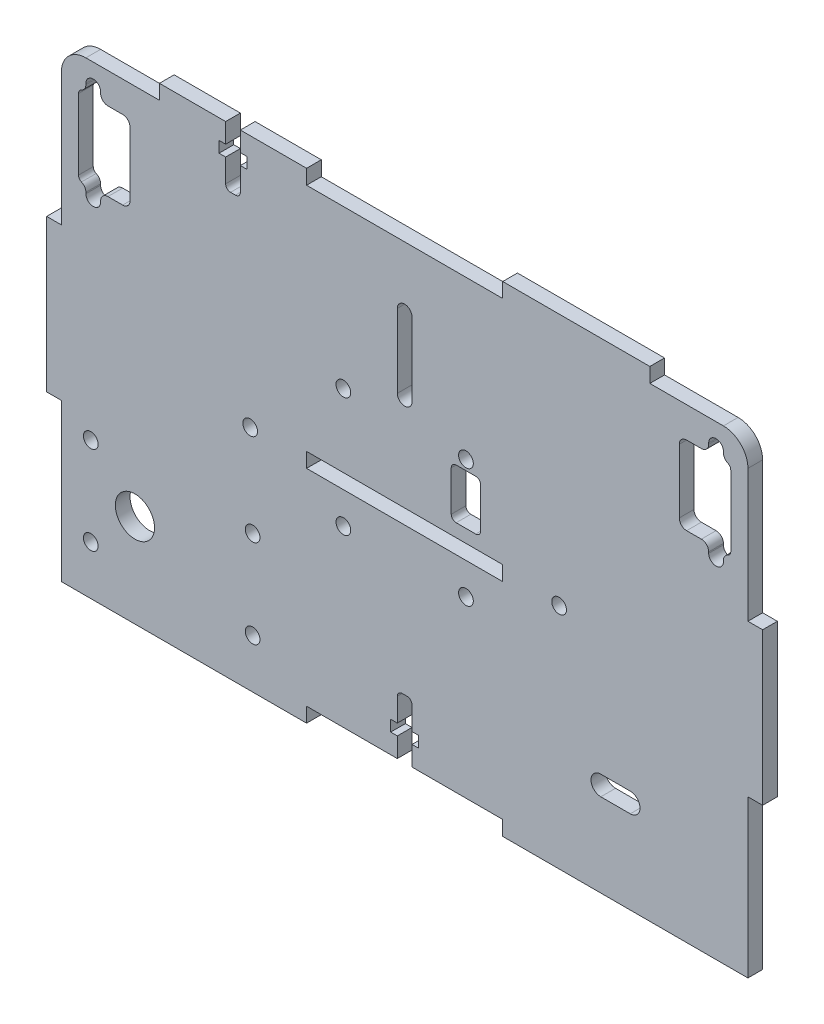
SolidWorks part; units mm, degrees
other "Marcação1"
sketch "Esboço7" plane through (-68, 31.5, 3) normal (-0.6758, 0.2828, 0.6807) x (0.7271, 0.1043, 0.6785)
sketch "Esboço8" plane through (-68, 31.5, 3) normal (-0.6758, 0.2828, 0.6807) x (0.7271, 0.1043, 0.6785)
sketch "Esboço9" plane through (-68, 31.5, 3) normal (-0.6758, 0.2828, 0.6807) x (0.7271, 0.1043, 0.6785)
sketch "Esboço10" plane through (-68, 31.5, 3) normal (-0.6758, 0.2828, 0.6807) x (0.7271, 0.1043, 0.6785)
sketch "Esboço11" plane through (-68, 36.25, 3) normal (-0.6758, 0.2828, 0.6807) x (0.7271, 0.1043, 0.6785)
sketch "Esboço13" plane through (-68, 36.25, 3) normal (-0.6758, 0.2828, 0.6807) x (0.7271, 0.1043, 0.6785)
sketch "Esboço15" plane through (-68, 36.25, 3) normal (-0.6758, 0.2828, 0.6807) x (0.7271, 0.1043, 0.6785)
sketch "Esboço19" plane through (-68, 66.25, 3) normal (-0.6758, 0.2828, 0.6807) x (0.7271, 0.1043, 0.6785)
sketch "Esboço22" plane through (-68, 95.5577, 3) normal (-0.6758, 0.2828, 0.6807) x (0.7271, 0.1043, 0.6785)
material "Acrylic (Medium-high impact)"
ref_plane "Plano frontal" through (0, 0, 0) normal (0, 0, 1) x (1, 0, 0)
ref_plane "Plano superior" through (0, 0, 0) normal (0, 1, 0) x (1, 0, 0)
ref_plane "Plano direito" through (0, 0, 0) normal (1, 0, 0) x (0, 0, -1)
sketch "Esboço1" plane through (0, 0, 0) normal (0, 0, 1) x (1, 0, 0)
  line L6 (70, -47.5) -> (-70, -47.5)
  line L8 (70, -47.5) -> (70, 47.5)
  line L9 (70, 47.5) -> (-70, 47.5)
  line L10 (-70, -47.5) -> (-70, 47.5)
  line L11 (70, -47.5) -> (-70, 47.5) construction
  line L12 (70, 47.5) -> (-70, -47.5) construction
  point P0 (0, 0)
  dimension "D1" = 95
  dimension "D2" = 140
extrude "Ressalto-extrusão1" add sketch "Esboço1" along normal mid plane 3
sketch "Esboço2" plane through (0, 0, 1.5) normal (0, 0, 1) x (1, 0, 0)
  line L1 (-20, -47.5) -> (20, -47.5)
  line L2 (-20, -47.5) -> (-20, -44.5)
  line L3 (-20, -44.5) -> (20, -44.5)
  line L4 (20, -47.5) -> (20, -44.5)
  line L6 (-70, -47.5) -> (70, -47.5) construction
  line L21 (-20, 0.5) -> (20, 0.5)
  line L22 (-20, 0.5) -> (-20, -2.5)
  line L23 (-20, -2.5) -> (20, -2.5)
  line L24 (20, 0.5) -> (20, -2.5)
  line L25 (-20, 0.5) -> (20, -2.5) construction
  line L26 (-20, -2.5) -> (20, 0.5) construction
  line L28 (0, -1.65) -> (0, 1.65) construction
  circle A2 centre (-31.5, -1) radius 1.5
  circle A4 centre (31.5, -1) radius 1.5
  point P6 (0, -44.5)
  point P14 (0, -1)
  point P29 (-20, -1)
  dimension "D4" = 3
  dimension "D8" = 3
  dimension "D9" = 10
  dimension "D2" = 40
  dimension "D3" = 45
  dimension "D6" = 3
  dimension "D13" = 40
extrude "Corte-extrusão1" cut sketch "Esboço2" against normal through all
sketch "Esboço3" plane through (0, 0, 1.5) normal (0, 0, 1) x (1, 0, 0)
  line L0 (70, -47.5) -> (70, 47.5) construction
  line L1 (70, 15.5) -> (73, 15.5)
  line L2 (70, 15.5) -> (70, -15.5)
  line L3 (70, -15.5) -> (73, -15.5)
  line L4 (73, 15.5) -> (73, -15.5)
  line L5 (0, -1.65) -> (0, 1.65) construction
  line L6 (-70, -15.5) -> (-73, -15.5)
  line L7 (-70, 15.5) -> (-73, 15.5)
  line L8 (-70, 15.5) -> (-70, -15.5)
  line L9 (-73, 15.5) -> (-73, -15.5)
  line L10 (70, 47.5) -> (-70, 47.5) construction
  line L11 (-50, 50.5) -> (-20, 50.5)
  line L12 (-50, 50.5) -> (-50, 47.5)
  line L13 (-50, 47.5) -> (-20, 47.5)
  line L14 (-20, 50.5) -> (-20, 47.5)
  line L15 (20, 50.5) -> (20, 47.5)
  line L16 (50, 47.5) -> (20, 47.5)
  line L17 (50, 50.5) -> (50, 47.5)
  line L18 (50, 50.5) -> (20, 50.5)
  line L19 (0, -37.5) -> (0, 37.5) construction
  line L20 (-70, 47.5) -> (-70, -47.5) construction
  point P6 (70, 0)
  point P28 (0, 0)
  dimension "D1" = 3
  dimension "D2" = 31
  dimension "D3" = 3
  dimension "D4" = 30
  dimension "D5" = 20
  dimension "D6" = 20
extrude "Ressalto-extrusão2" add sketch "Esboço3" against normal through all
sketch "Esboço30" plane through (0, 0, -1.5) normal (0, 0, -1) x (-1, 0, 0)
  line L0 (73, 15.5) -> (73, -15.5) construction
  line L1 (70, -47.5) -> (20, -47.5) construction
  circle A0 centre (55, -28.5) radius 4
  dimension "D1" = 8
  dimension "D2" = 18
  dimension "D3" = 19
extrude "Corte-extrusão11" cut sketch "Esboço30" against normal through all both and the other way through all
sketch "Esboço31" plane through (0, 0, -1.5) normal (0, 0, -1) x (-1, 0, 0)
  circle A4 centre (64, -19.5) radius 1.5
  circle A5 centre (64, -37.5) radius 1.5
  circle A6 centre (55, -28.5) radius 4 construction
  circle A7 centre (31, -19.5) radius 1.5
  circle A8 centre (31, -37.5) radius 1.5
  dimension "D1" = 3
  dimension "D2" = 9
  dimension "D3" = 9
  dimension "D4" = 18
  dimension "D5" = 33
extrude "Corte-extrusão12" cut sketch "Esboço31" against normal through all both and the other way through all
sketch "Esboço4" plane through (0, 0, 1.5) normal (0, 0, 1) x (1, 0, 0)
  line L0 (-59, -28.5) -> (-51, -28.5) construction
  line L1 (40, -28.5) -> (46, -28.5) construction
  line L2 (40, -26.5) -> (46, -26.5)
  line L3 (40, -30.5) -> (46, -30.5)
  circle A9 centre (-55, -28.5) radius 4 construction
  circle A10 centre (43, -28.5) radius 2 construction
  arc A11 (40, -26.5) -> (40, -30.5) centre (40, -28.5) ccw
  arc A12 (46, -30.5) -> (46, -26.5) centre (46, -28.5) ccw
  point P9 (43, -28.5)
  dimension "D1" = 98
  dimension "D2" = 4
  dimension "D3" = 3
extrude "Corte-extrusão2" cut sketch "Esboço4" against normal through all
sketch "Sketch5" plane through (0, 0, 0) normal (0, 0, 1) x (1, 0, 0)
  line L0 (20, -44.5) -> (-20, -44.5) construction
  line L1 (-1.5, -44.5) -> (1.5, -44.5)
  line L2 (-1.5, -44.5) -> (-1.5, -40.5)
  line L3 (-0.5, -32.5) -> (0.5, -32.5)
  line L4 (1.5, -44.5) -> (1.5, -40.5)
  line L5 (1.5, -38.23) -> (2.85, -38.23)
  line L6 (-2.85, -38.23) -> (-1.5, -38.23)
  line L7 (-2.85, -38.23) -> (-2.85, -40.5)
  line L8 (-2.85, -40.5) -> (-1.5, -40.5)
  line L9 (2.85, -38.23) -> (2.85, -40.5)
  line L10 (-1.5, -38.23) -> (-1.5, -33.5)
  line L11 (1.5, -40.5) -> (2.85, -40.5)
  line L12 (1.5, -38.23) -> (1.5, -33.5)
  arc A0 (0.5, -32.5) -> (1.5, -33.5) centre (0.5, -33.5) cw
  arc A1 (-1.5, -33.5) -> (-0.5, -32.5) centre (-0.5, -33.5) cw
  point P6 (0, -32.5)
  point P18 (1.5, -32.5)
  point P21 (-1.5, -32.5)
  dimension "D7" = 1
  dimension "D1" = 12
  dimension "D2" = 3
  dimension "D3" = 2.27
  dimension "D4" = 1.35
  dimension "D5" = 1.35
  dimension "D6" = 4
extrude "Cut-Extrude2" cut sketch "Sketch5" against normal through all both and the other way through all
sketch "Sketch8" plane through (0, 0, 1.5) normal (0, 0, 1) x (1, 0, 0)
  line L12 (0, -1.65) -> (0, 1.65) construction
  line L13 (-70, 47.5) -> (-70, 15.5) construction
  line L14 (70, 47.5) -> (50, 47.5) construction
  line B0 (-70, 33.25) -> (-56, 33.25) construction
  line B1 (-68.5, 41.25) -> (-66.5, 41.25) construction
  line B2 (-70, 39.75) -> (-70, 26.75) construction
  line B3 (-68.5, 25.25) -> (-66.5, 25.25) construction
  line B4 (-56, 39.75) -> (-56, 26.75)
  line B5 (-65, 23.5) -> (-65, 23.75)
  line B6 (-62, 23.5) -> (-62, 23.75)
  line B7 (-60.5, 25.25) -> (-57.5, 25.25)
  line B8 (-65, 43) -> (-65, 42.75)
  line B9 (-62, 43) -> (-62, 42.75)
  line B10 (-60.5, 41.25) -> (-57.5, 41.25)
  line B11 (-66.5, 40.4587) -> (-66.5, 26.0413)
  arc B12 (-62, 43) -> (-65, 43) centre (-63.5, 43) ccw
  arc B13 (-65, 23.5) -> (-62, 23.5) centre (-63.5, 23.5) ccw
  arc B14 (-62, 23.75) -> (-60.5, 25.25) centre (-60.5, 23.75) cw
  arc B15 (-65, 23.75) -> (-65.9, 25.1248) centre (-66.5, 23.75) ccw
  arc B16 (-62, 42.75) -> (-60.5, 41.25) centre (-60.5, 42.75) ccw
  arc B17 (-65, 42.75) -> (-65.9, 41.3752) centre (-66.5, 42.75) cw
  arc B18 (-70, 26.75) -> (-68.5, 25.25) centre (-68.5, 26.75) ccw construction
  arc B19 (-57.5, 25.25) -> (-56, 26.75) centre (-57.5, 26.75) ccw
  arc B20 (-57.5, 41.25) -> (-56, 39.75) centre (-57.5, 39.75) cw
  arc B21 (-68.5, 41.25) -> (-70, 39.75) centre (-68.5, 39.75) ccw construction
  arc B22 (-66.5, 26.0413) -> (-65.9, 25.1248) centre (-65.5, 26.0413) ccw
  arc B23 (-66.5, 40.4587) -> (-65.9, 41.3752) centre (-65.5, 40.4587) cw
  line B24 (56, 39.75) -> (56, 26.75)
  line B25 (65, 23.5) -> (65, 23.75)
  line B26 (62, 23.5) -> (62, 23.75)
  line B27 (60.5, 25.25) -> (57.5, 25.25)
  line B28 (65, 43) -> (65, 42.75)
  line B29 (62, 43) -> (62, 42.75)
  line B30 (60.5, 41.25) -> (57.5, 41.25)
  line B31 (66.5, 40.4587) -> (66.5, 26.0413)
  arc B32 (62, 43) -> (65, 43) centre (63.5, 43) cw
  arc B33 (65, 23.5) -> (62, 23.5) centre (63.5, 23.5) cw
  arc B34 (62, 23.75) -> (60.5, 25.25) centre (60.5, 23.75) ccw
  arc B35 (65, 23.75) -> (65.9, 25.1248) centre (66.5, 23.75) cw
  arc B36 (62, 42.75) -> (60.5, 41.25) centre (60.5, 42.75) cw
  arc B37 (65, 42.75) -> (65.9, 41.3752) centre (66.5, 42.75) ccw
  arc B38 (57.5, 25.25) -> (56, 26.75) centre (57.5, 26.75) cw
  arc B39 (57.5, 41.25) -> (56, 39.75) centre (57.5, 39.75) ccw
  arc B40 (66.5, 26.0413) -> (65.9, 25.1248) centre (65.5, 26.0413) cw
  arc B41 (66.5, 40.4587) -> (65.9, 41.3752) centre (65.5, 40.4587) ccw
  dimension "D1" = 3
sketch_block_instance "Block6-1"
sketch_block "Block6" parameters "D1"=3, "D2"=1.5, "D3"=1.5, "D5"=1, "D4"=5, "D6"=12
sketch_block_instance "Block6-2"
extrude "Cut-Extrude6" cut sketch "Sketch8" against normal through all both and the other way through all
sketch "Sketch11" plane through (0, 0, 0) normal (0, 0, 1) x (1, 0, 0)
  line L0 (-20, 50.5) -> (-50, 50.5) construction
  line L1 (-36.5, 50.5) -> (-33.5, 50.5)
  line L2 (-36.5, 50.5) -> (-36.5, 46.5)
  line L3 (-35.5, 38.5) -> (-34.5, 38.5)
  line L4 (-33.5, 50.5) -> (-33.5, 46.5)
  line L5 (-50, 50.5) -> (-50, 47.5) construction
  line L6 (-33.5, 46.5) -> (-32.15, 46.5)
  line L7 (-37.85, 46.5) -> (-36.5, 46.5)
  line L8 (-37.85, 46.5) -> (-37.85, 44.23)
  line L9 (-37.85, 44.23) -> (-36.5, 44.23)
  line L10 (-32.15, 46.5) -> (-32.15, 44.23)
  line L11 (-36.5, 44.23) -> (-36.5, 39.5)
  line L12 (-33.5, 44.23) -> (-33.5, 39.5)
  line L13 (-33.5, 44.23) -> (-32.15, 44.23)
  arc A0 (-34.5, 38.5) -> (-33.5, 39.5) centre (-34.5, 39.5) ccw
  arc A1 (-36.5, 39.5) -> (-35.5, 38.5) centre (-35.5, 39.5) ccw
  point P12 (-36.5, 38.5)
  dimension "D4" = 1
  dimension "D1" = 3
  dimension "D2" = 12
  dimension "D3" = 13.5
  dimension "D5" = 4
  dimension "D6" = 2.27
  dimension "D7" = 1.35
  dimension "D8" = 1.35
extrude "Cut-Extrude8" cut sketch "Sketch11" against normal through all both and the other way through all
sketch "Sketch12" plane through (0, 0, 1.5) normal (0, 0, 1) x (1, 0, 0)
  line L0 (0, 0.5) -> (0, 47.5) construction
  line L1 (20, 0.5) -> (-20, 0.5) construction
  line L3 (20, 47.5) -> (-20, 47.5) construction
  line L4 (0, 20) -> (0, 35) construction
  line L7 (-1.5, 20) -> (-1.5, 35)
  line L8 (1.5, 20) -> (1.5, 35)
  circle A1 centre (0, 20) radius 1.5 construction
  arc A4 (-1.5, 20) -> (1.5, 20) centre (0, 20) ccw
  arc A5 (1.5, 35) -> (-1.5, 35) centre (0, 35) ccw
  point P6 (0, 27.5)
  dimension "D1" = 3
  dimension "D2" = 15
  dimension "D3" = 18
extrude "Cut-Extrude9" cut sketch "Sketch12" against normal through all
sketch "Sketch16" plane through (0, 0, 0) normal (0, 0, 1) x (1, 0, 0)
  line L1 (20, 0.5) -> (-20, 0.5) construction
  line L2 (-20, 0.5) -> (-20, -2.5) construction
  line L4 (10.5, 13.35) -> (14.5, 13.35)
  line L5 (9.5, 12.35) -> (9.5, 4.15)
  line L6 (10.5, 3.15) -> (14.5, 3.15)
  line L7 (15.5, 12.35) -> (15.5, 4.15)
  circle A0 centre (-12.5, 15.35) radius 1.5
  circle A1 centre (12.5, 15.35) radius 1.5
  circle A2 centre (-12.5, -8.95) radius 1.5
  circle A3 centre (12.5, -8.95) radius 1.5
  arc A4 (9.5, 4.15) -> (10.5, 3.15) centre (10.5, 4.15) ccw
  arc A5 (14.5, 3.15) -> (15.5, 4.15) centre (14.5, 4.15) ccw
  arc A6 (14.5, 13.35) -> (15.5, 12.35) centre (14.5, 12.35) cw
  arc A7 (10.5, 13.35) -> (9.5, 12.35) centre (10.5, 12.35) ccw
  point P8 (12.5, 13.35)
  point P21 (15.5, 3.15)
  point P24 (15.5, 13.35)
  dimension "D1" = 3
  dimension "D2" = 25
  dimension "D3" = 24.3
  dimension "D4" = 13.35
  dimension "D5" = 7.5
  dimension "D7" = 1.5
  dimension "D9" = 1
  dimension "D6" = 0.5
  dimension "D8" = 10.2
extrude "Cut-Extrude12" cut sketch "Sketch16" against normal through all both and the other way through all
fillet "Fillet1" radius 5 2 edges at (-70, 47.5, 0) (70, 47.5, 0)
